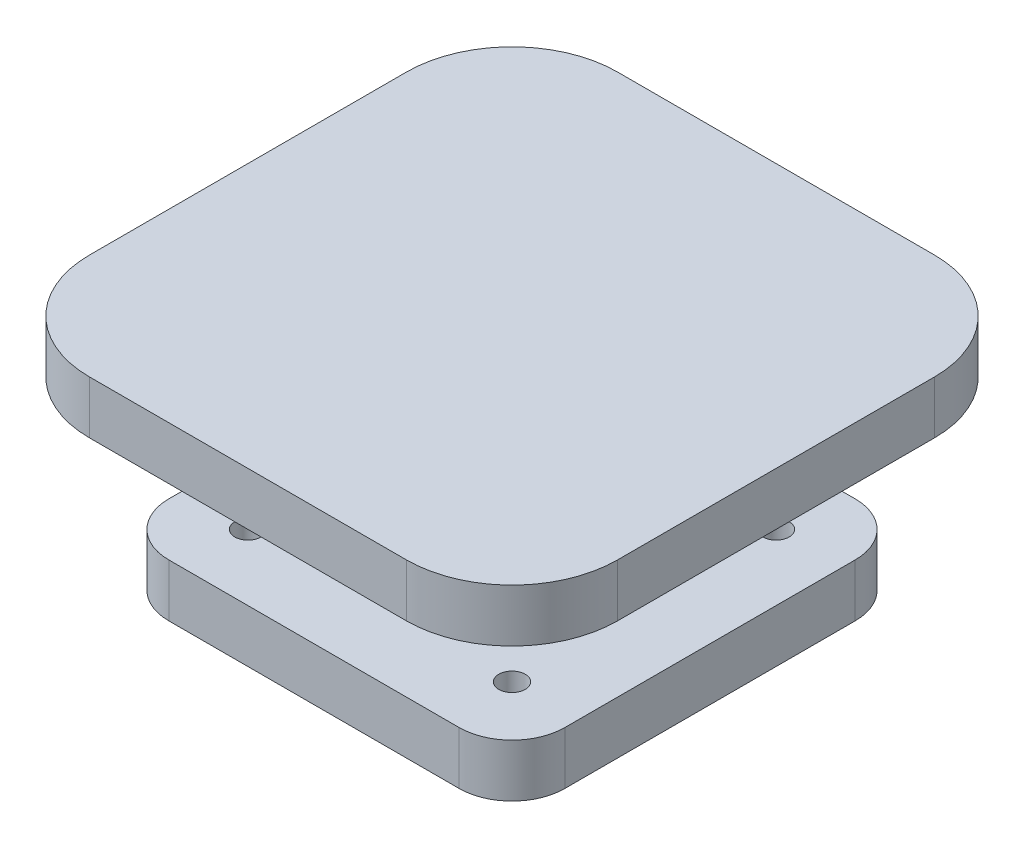
SolidWorks part; units mm, degrees
ref_plane "Спереди" through (0, 0, 0) normal (0, 0, 1) x (1, 0, 0)
ref_plane "Сверху" through (0, 0, 0) normal (0, 1, 0) x (1, 0, 0)
ref_plane "Справа" through (0, 0, 0) normal (1, 0, 0) x (0, 0, -1)
sketch "Эскиз1" plane through (0, 0, 0) normal (0, 1, 0) x (1, 0, 0)
  line L1 (-50, -50) -> (50, -50)
  line L2 (-50, -50) -> (-50, 50)
  line L3 (-50, 50) -> (50, 50)
  line L4 (50, -50) -> (50, 50)
  line L5 (-50, -50) -> (50, 50) construction
  line L6 (-50, 50) -> (50, -50) construction
  line L7 (-75, -75) -> (75, -75)
  line L8 (-75, -75) -> (-75, 75)
  line L9 (-75, 75) -> (75, 75)
  line L10 (75, -75) -> (75, 75)
  line L11 (-75, -75) -> (75, 75) construction
  line L12 (-75, 75) -> (75, -75) construction
  circle A0 centre (-50, 50) radius 5
  circle A1 centre (50, 50) radius 5
  circle A2 centre (50, -50) radius 5
  circle A3 centre (-50, -50) radius 5
  point P0 (0, 0)
  point P10 (0, 0)
  dimension "D2" = 10
  dimension "D1" = 100
  dimension "D3" = 150
extrude "Бобышка-Вытянуть1" add sketch "Эскиз1" along normal blind 20 contours L7 L10 L9 L8 A3 L2 A0 L3 A1 L4 A2 L1 | A3 L1 A2 L4 A1 L3 A0 L2
fillet "Скругление1" radius 20 4 edges at (-75, 10, -75) (75, 10, -75) (75, 10, 75) (-75, 10, 75)
sketch "Эскиз2" plane through (0, 20, 0) normal (0, 1, 0) x (1, 0, 0)
  circle A0 centre (0, 0) radius 50
  dimension "D1" = 100
extrude "Бобышка-Вытянуть2" add sketch "Эскиз2" along normal blind 50
sketch "Эскиз3" plane through (0, 70, 0) normal (0, 1, 0) x (1, 0, 0)
  line L1 (-100, -100) -> (100, -100)
  line L2 (-100, -100) -> (-100, 100)
  line L3 (-100, 100) -> (100, 100)
  line L4 (100, -100) -> (100, 100)
  line L5 (-100, -100) -> (100, 100) construction
  line L6 (-100, 100) -> (100, -100) construction
  point P0 (0, 0)
  dimension "D1" = 200
extrude "Бобышка-Вытянуть3" add sketch "Эскиз3" along normal blind 20
fillet "Скругление2" radius 40 4 edges at (-100, 80, -100) (-100, 80, 100) (100, 80, 100) (100, 80, -100)
